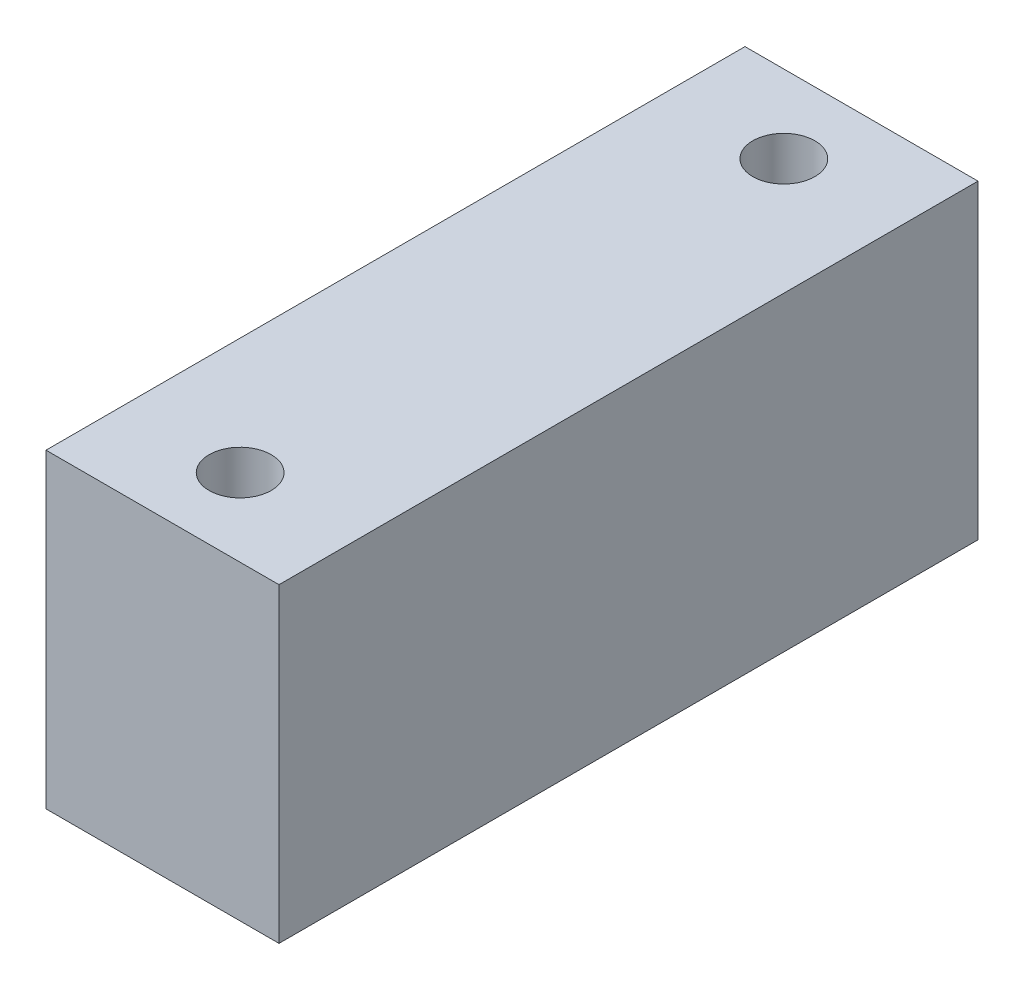
SolidWorks part; units mm, degrees
ref_plane "Front Plane" through (0, 0, 0) normal (0, 0, 1) x (1, 0, 0)
ref_plane "Top Plane" through (0, 0, 0) normal (0, 1, 0) x (1, 0, 0)
ref_plane "Right Plane" through (0, 0, 0) normal (1, 0, 0) x (0, 0, -1)
sketch "Sketch1" plane through (0, 0, 0) normal (0, 1, 0) x (1, 0, 0)
  line L0 (0, 45) -> (0, -45) construction
  line L1 (-15, -45) -> (15, -45)
  line L2 (-15, -45) -> (-15, 45)
  line L3 (-15, 45) -> (15, 45)
  line L4 (15, -45) -> (15, 45)
  line L5 (-15, -45) -> (15, 45) construction
  line L6 (-15, 45) -> (15, -45) construction
  line L7 (-15, 0) -> (15, 0) construction
  circle A0 centre (0, 35) radius 4
  circle A1 centre (0, -35) radius 4
  point P0 (0, 0)
  dimension "D2" = 8
  dimension "D4" = 70
  dimension "D1" = 90
  dimension "D3" = 30
extrude "Boss-Extrude1" add sketch "Sketch1" along normal blind 40
